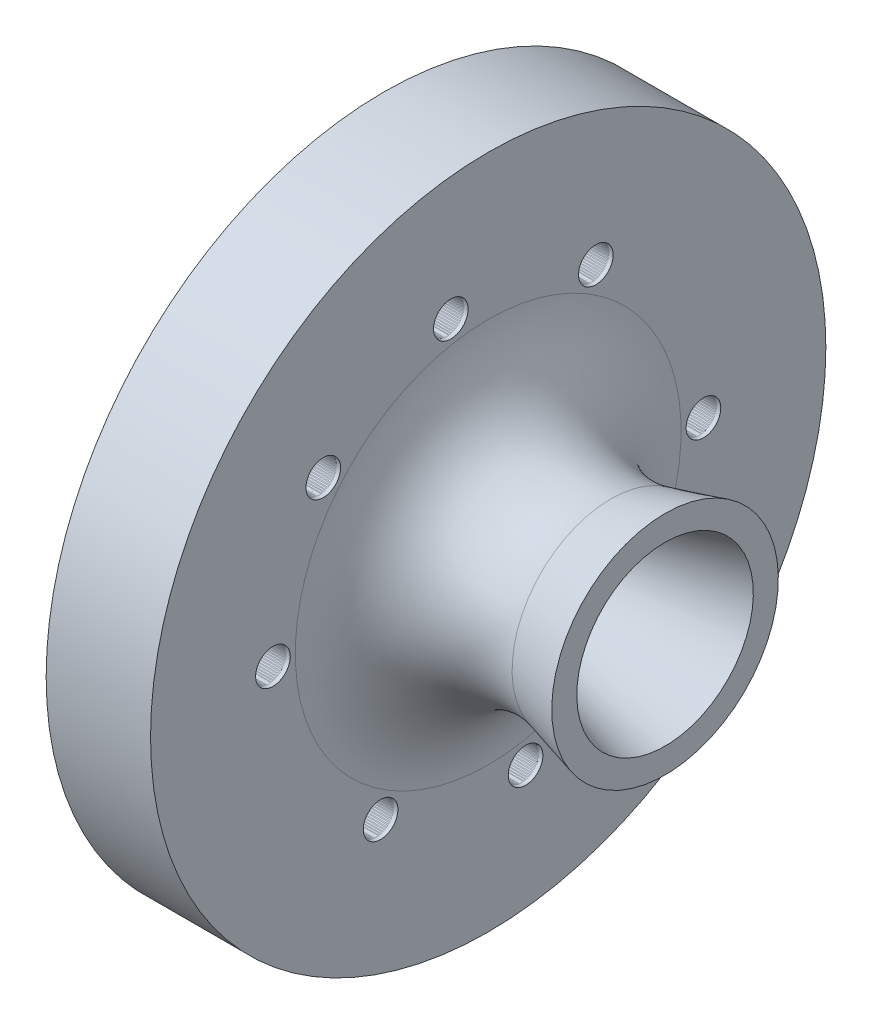
SolidWorks part; units mm, degrees
material "ABS"
ref_plane "Front Plane" through (0, 0, 0) normal (0, 0, 1) x (1, 0, 0)
ref_plane "Top Plane" through (0, 0, 0) normal (0, 1, 0) x (1, 0, 0)
ref_plane "Right Plane" through (0, 0, 0) normal (1, 0, 0) x (0, 0, -1)
sketch "Sketch2" plane through (0, 0, 0) normal (0, 0, 1) x (1, 0, 0)
  line L0 (-4.3942, 4.3942) -> (0, 0)
  line L1 (0, 0) -> (16.696, 4.4732)
  line L2 (16.696, 4.4732) -> (16.696, -3.8608) construction
  line L3 (16.696, -3.8608) -> (-4.3942, -3.8608) construction
  line L4 (-4.3942, -3.8608) -> (-4.3942, 4.3942) construction
  line L5 (-4.3942, 6.7564) -> (-4.3942, 4.3942)
  line L7 (0, 2.3622) -> (16.696, 6.8354)
  line L8 (16.696, 6.8354) -> (16.696, 4.4732)
  line L9 (0, 2.3622) -> (0, 0) construction
  line L10 (-9.8552, 28.0154) -> (0, 28.0154)
  line L11 (0, 28.0154) -> (0, 2.3622)
  line L12 (-10.2362, 28.0154) -> (-9.8552, 28.0154) construction
  line L13 (-9.8552, 28.0154) -> (-9.8552, 11.9792) construction
  line L14 (-9.8552, 11.9792) -> (-7.5692, 11.9792) construction
  line L15 (-7.5692, 11.9792) -> (-7.5692, 10.7492) construction
  line L16 (-7.5692, 10.7492) -> (-4.3942, 10.7492) construction
  line L17 (-10.2362, 4.3934) -> (-11.4712, 4.3934) construction
  line L18 (-4.3942, 10.7492) -> (-4.3942, 8.8892) construction
  line L19 (-4.3942, 4.3934) -> (-10.2362, 4.3934) construction
  line L20 (-10.2362, 4.3934) -> (-10.2362, 28.0154) construction
  line L21 (-4.3942, 8.8892) -> (-5.6896, 8.8892) construction
  line L22 (-5.6896, 8.8892) -> (-5.6896, 6.7556) construction
  line L23 (-5.6896, 6.7556) -> (-4.3942, 6.7556) construction
  line L24 (-4.3942, 6.7556) -> (-4.3942, 4.3934) construction
  line L25 (-9.8552, 28.0154) -> (-9.8552, 11.9792)
  line L26 (-9.8552, 11.9792) -> (-7.5692, 11.9792)
  line L27 (-7.5692, 11.9792) -> (-7.5692, 10.7492)
  line L28 (-7.5692, 10.7492) -> (-4.3942, 10.7492)
  line L29 (-4.3942, 10.7492) -> (-4.3942, 8.8892)
  line L30 (-4.3942, 8.8892) -> (-5.6896, 8.8892)
  line L31 (-5.6896, 8.8892) -> (-5.6896, 6.7556)
  line L32 (-5.6896, 6.7556) -> (-4.3942, 6.7564)
  dimension "D1" = 3.8608
  dimension "D2" = 8.334
  dimension "D3" = 16.696
  dimension "D4" = 45
  dimension "D5" = 2.3622
  dimension "D6" = 8.255
  dimension "D7" = 2.1336
  dimension "D8" = 23.622
  dimension "D9" = 0.381
  dimension "D10" = 2.286
  dimension "D12" = 14.61
  dimension "D13" = 2.3622
  dimension "D14" = 15.84
  dimension "D15" = 12.75
  dimension "D16" = 3.175
  dimension "D17" = 1.2954
revolve "Revolve1" add sketch "Sketch2" angle 360 about L3
sketch "Sketch3" plane through (-4.3942, 0, 0) normal (-1, 0, 0) x (0, 0, 1)
  circle A0 centre (0, -3.8608) radius 23.622
  circle A1 centre (0, -3.8608) radius 10.6172
  dimension "D1" = 47.244
  dimension "D2" = 21.2344
extrude "Boss-Extrude1" add sketch "Sketch3" against normal blind 4 separate body
sketch "Sketch9" plane through (0, 0, 0) normal (1, 0, 0) x (0, 0, -1)
  line L0 (0, -3.8608) -> (39.7201, -3.8608) construction
  line L1 (0, -3.8608) -> (0, 28.0154) construction
sketch "Sketch10" plane through (-4.3942, 0, 0) normal (-1, 0, 0) x (0, 0, 1)
  line L1 (-50.7274, -3.8608) -> (50.7274, -3.8608) construction
  line L2 (0, 29.7895) -> (0, -37.5111) construction
  line L3 (0, -3.8608) -> (-20.32, -3.8608) construction
  line L4 (0, -3.8608) -> (-10.16, -3.8608) construction
  line L5 (-10.16, -3.8608) -> (-10.16, 13.7392) construction
  line L6 (0, -3.8608) -> (-3.53, -23.8708) construction
  line L7 (-3.53, -23.8708) -> (0, -23.8708) construction
  line L8 (0, -23.8708) -> (0, -3.8608) construction
  line L9 (0, -3.8608) -> (0, 9.1992) construction
  line L10 (0, 9.1992) -> (15.57, 9.1992) construction
  circle A0 centre (-10.16, 13.7392) radius 1.635
  circle A1 centre (3.53, 16.1492) radius 1.635
  circle A2 centre (20.32, -3.8608) radius 1.635
  circle A3 centre (10.16, -21.4608) radius 1.635
  circle A4 centre (-3.53, -23.8708) radius 1.635
  circle A6 centre (-15.57, -16.9208) radius 1.635
  circle A7 centre (-20.32, -3.8608) radius 1.635
  circle A8 centre (15.57, 9.1992) radius 1.635
  point P7 (0, -3.8608)
  point P10 (0, -3.8608)
  point P12 (0, -3.8608)
  point P13 (20.32, -3.8608)
  point P18 (10.16, -21.4608)
  point P24 (-15.57, -16.9208)
  point P26 (3.53, 16.1492)
  dimension "D1" = 3.27
  dimension "D8" = 3.27
  dimension "D9" = 3.27
  dimension "D10" = 3.27
  dimension "D11" = 3.27
  dimension "D12" = 3.27
  dimension "D13" = 3.27
  dimension "D14" = 3.27
  dimension "D15" = 17.6
  dimension "D2" = 20.32
  dimension "D3" = 10.16
  dimension "D4" = 20.01
  dimension "D5" = 3.53
  dimension "D6" = 15.57
  dimension "D7" = 13.06
extrude "Cut-Extrude1" cut sketch "Sketch10" against normal up to surface and the other way through all
fillet "Fillet2" radius 9.2 1 edges at (0, 2.3622, 0)
sketch "Sketch11" plane through (-9.8552, 0, 0) normal (-1, 0, 0) x (0, 0, 1)
  line L0 (-10.16, 13.7392) -> (-20.32, -3.8608) construction
  line L5 (-14.034, 7.0283) -> (-16.2334, 3.2183)
  line L6 (-14.034, 7.0283) -> (-17.3337, 8.9331)
  line L7 (-16.2334, 3.2183) -> (-19.5331, 5.1231)
  line L8 (-17.3337, 8.9331) -> (-19.5331, 5.1231)
  dimension "D1" = 3.81
  dimension "D2" = 3.81
  dimension "D3" = 6.7109
extrude "Cut-Extrude2" cut sketch "Sketch11" against normal blind 1.27
